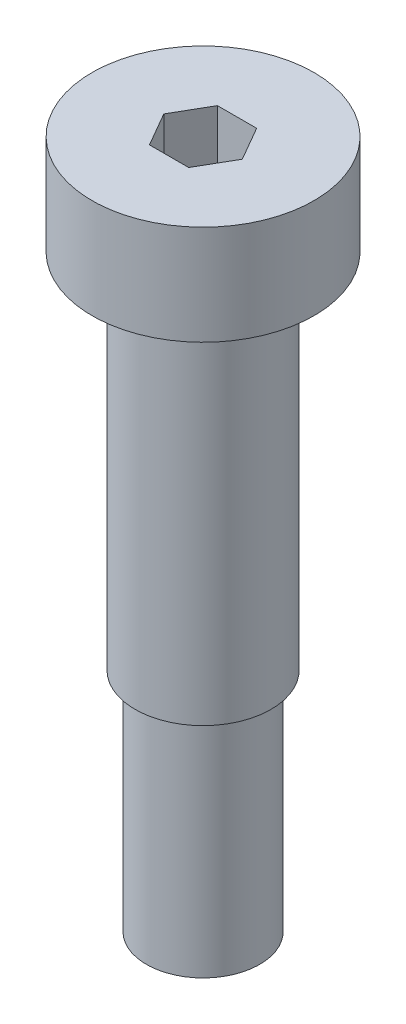
SolidWorks part; units mm, degrees
ref_plane "前视基准面" through (0, 0, 0) normal (0, 0, 1) x (1, 0, 0)
ref_plane "上视基准面" through (0, 0, 0) normal (0, 1, 0) x (1, 0, 0)
ref_plane "右视基准面" through (0, 0, 0) normal (1, 0, 0) x (0, 0, -1)
sketch "草图1" plane through (0, 0, 0) normal (0, 0, 1) x (1, 0, 0)
  line L0 (0, 0) -> (0, 30.4)
  line L1 (0, 30.4) -> (4.9, 30.4)
  line L2 (4.9, 30.4) -> (4.9, 26)
  line L3 (4.9, 26) -> (3, 26)
  line L4 (3, 26) -> (3, 10)
  line L5 (3, 10) -> (2.5, 10)
  line L6 (2.5, 10) -> (2.5, 0)
  line L7 (2.5, 0) -> (0, 0)
  dimension "D1" = 4.4
  dimension "D2" = 4.9
  dimension "D3" = 10
  dimension "D4" = 2.5
  dimension "D5" = 3
  dimension "D6" = 16
revolve "旋转1" add sketch "草图1" angle 360 about L0
cosmetic thread "装饰螺纹线1"
sketch "草图2" plane through (0, 30.4, 0) normal (0, 1, 0) x (1, 0, 0)
  line L1 (1.7321, 0) -> (0.866, 1.5)
  line L2 (0.866, 1.5) -> (-0.866, 1.5)
  line L3 (-0.866, 1.5) -> (-1.7321, 0)
  line L4 (-1.7321, 0) -> (-0.866, -1.5)
  line L5 (-0.866, -1.5) -> (0.866, -1.5)
  line L6 (0.866, -1.5) -> (1.7321, 0)
  circle A0 centre (0, 0) radius 1.5 construction
  dimension "D1" = 3
extrude "切除-拉伸1" cut sketch "草图2" against normal blind 3
sketch "草图3" plane through (0, 30.4, 0) normal (0, 1, 0) x (1, 0, 0)
  line L0 (-4.2952, 0) -> (0.1468, 0)
